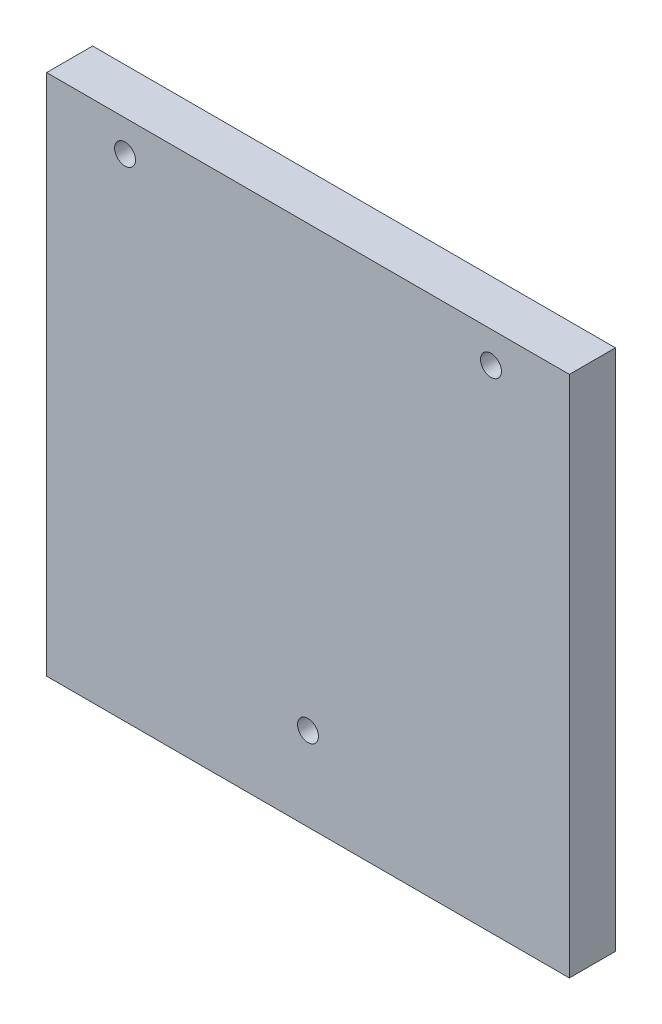
SolidWorks part; units mm, degrees
material "Pin"
ref_plane "Plan de face" through (0, 0, 0) normal (0, 0, 1) x (1, 0, 0)
ref_plane "Plan de dessus" through (0, 0, 0) normal (0, 1, 0) x (1, 0, 0)
ref_plane "Plan de droite" through (0, 0, 0) normal (1, 0, 0) x (0, 0, -1)
sketch "Esquisse1" plane through (0, 0, 0) normal (0, 0, 1) x (1, 0, 0)
  line L1 (125, -125) -> (-125, -125)
  line L2 (125, -125) -> (125, 125)
  line L3 (125, 125) -> (-125, 125)
  line L4 (-125, -125) -> (-125, 125)
  line L5 (125, -125) -> (-125, 125) construction
  line L6 (125, 125) -> (-125, -125) construction
  point P0 (0, 0)
  dimension "D1" = 250
  dimension "D2" = 250
extrude "Boss.-Extru.1" add sketch "Esquisse1" along normal blind 22
hole_wizard "Dégagement M81" positions "Esquisse2" profile "Esquisse3" hole size "M8" standard "ISO"
sketch "Esquisse2" plane through (0, 110, -30) normal (0, 0, -1) x (-1, 0, 0)
  point P0 (-87.5, 0)
  point P2 (87.5, 0)
  point P4 (0, -195)
  point P11 (0, 0)
  point P12 (0, 0)
sketch "Esquisse3" plane through (87.5, 110, -30) normal (1, 0, 0) x (0, 1, 0)
  line L0 (0, 0) -> (0, 211.0043)
  line L1 (0, 211.0043) -> (5, 208)
  line L2 (5, 208) -> (5, 0)
  line L3 (5, 0) -> (0, 0)
  line L4 (0, 211.0043) -> (-5, 208) construction
  line L5 (0, -6.35) -> (0, 107.95) construction
  dimension "Diamètre du perçage" = 10
  dimension "Profondeur du perçage" = 208
  dimension "Angle de pointe" = 118
